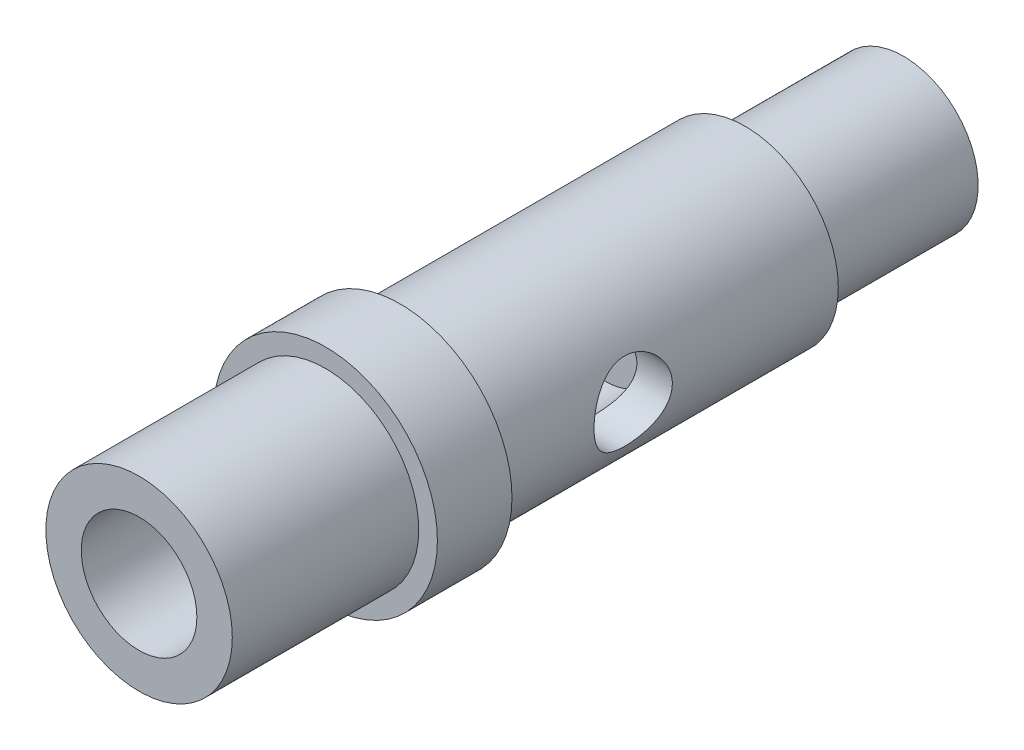
SolidWorks part; units mm, degrees
material "1060 合金"
ref_plane "正面" through (0, 0, 0) normal (0, 0, 1) x (1, 0, 0)
ref_plane "平面" through (0, 0, 0) normal (0, 1, 0) x (1, 0, 0)
ref_plane "右側面" through (0, 0, 0) normal (1, 0, 0) x (0, 0, -1)
sketch "ｽｹｯﾁ1" plane through (0, 0, 0) normal (0, 0, 1) x (1, 0, 0)
  circle A0 centre (0, 0) radius 5
  dimension "D1" = 10
extrude "ﾎﾞｽ - 押し出し1" add sketch "ｽｹｯﾁ1" along normal blind 18.5
sketch "ｽｹｯﾁ2" plane through (0, 0, 18.5) normal (0, 0, 1) x (1, 0, 0)
  circle A0 centre (0, 0) radius 6
  dimension "D1" = 12
extrude "ﾎﾞｽ - 押し出し2" add sketch "ｽｹｯﾁ2" along normal blind 4
sketch "ｽｹｯﾁ3" plane through (0, 0, 22.5) normal (0, 0, 1) x (1, 0, 0)
  circle A0 centre (0, 0) radius 5
  dimension "D1" = 10
extrude "ﾎﾞｽ - 押し出し3" add sketch "ｽｹｯﾁ3" along normal blind 10
sketch "ｽｹｯﾁ5" plane through (0, 0, 32.5) normal (0, 0, 1) x (1, 0, 0)
  circle A0 centre (0, 0) radius 3.1
  dimension "D1" = 6.2
extrude "ｶｯﾄ - 押し出し2" cut sketch "ｽｹｯﾁ5" against normal blind 25
sketch "ｽｹｯﾁ6" plane through (0, 0, 0) normal (1, 0, 0) x (0, 0, -1)
  line L0 (-18.5, 0) -> (-11, 0) construction
  line L1 (-18.5, -5) -> (-18.5, 5) construction
  circle A0 centre (-11, 0) radius 2.1
  dimension "D1" = 7.5
  dimension "D2" = 4.2
extrude "ｶｯﾄ - 押し出し3" cut sketch "ｽｹｯﾁ6" against normal through all both and the other way through all
sketch "ｽｹｯﾁ7" plane through (0, 0, 0) normal (0, 0, -1) x (-1, 0, 0)
  circle A0 centre (0, 0) radius 4
  dimension "D1" = 8
extrude "ﾎﾞｽ - 押し出し4" add sketch "ｽｹｯﾁ7" along normal blind 8.5
sketch "ｽｹｯﾁ4" plane through (0, 0, 32.5) normal (0, 0, 1) x (1, 0, 0)
  circle A0 centre (0, 0) radius 1.6
  dimension "D1" = 3.2
extrude "ｶｯﾄ - 押し出し1" cut sketch "ｽｹｯﾁ4" against normal through all
